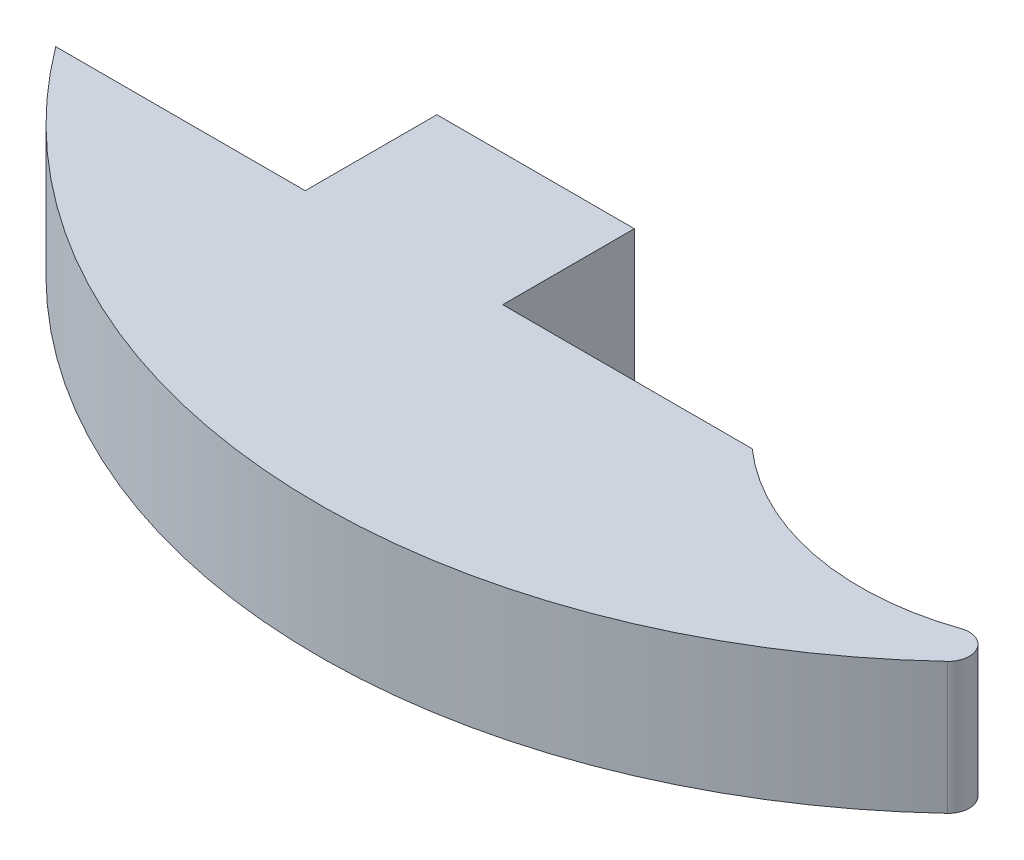
SolidWorks part; units mm, degrees
material "AISI 4130 Steel, annealed at 865C"
ref_plane "X-Y Datum" through (0, 0, 0) normal (0, 0, 1) x (1, 0, 0)
ref_plane "X-Z Datum" through (0, 0, 0) normal (0, 1, 0) x (1, 0, 0)
ref_plane "Y-Z Datum" through (0, 0, 0) normal (1, 0, 0) x (0, 0, -1)
sketch "Sketch1" plane through (0, 0, 0) normal (0, 1, 0) x (1, 0, 0)
  line L0 (-50.9024, -40.0059) -> (-57.5024, -40.0059) construction
  line L1 (-66.9024, -43.1809) -> (-20.6094, -43.1809)
  line L2 (-54.2024, -41.3694) -> (-54.2024, -38.6423) construction
  line L5 (-41.5024, -43.1809) -> (-66.9024, -43.1809)
  line L6 (-54.2024, -43.1809) -> (-54.2024, -48.3956) construction
  line L7 (-66.9024, -36.8309) -> (-66.9024, -43.1809)
  arc A3 (-12.2092, -46.3559) -> (-12.2092, -20.9559) centre (-12.2092, -33.6559) ccw construction
  arc A6 (-1.183, -39.9577) -> (-54.2024, -43.1809) centre (-28.7484, -24.2031) cw
  circle A7 centre (-12.2092, -33.6559) radius 12.7
  circle A8 centre (-12.2092, -33.6559) radius 12.7
  point P3 (-54.2024, -40.0059)
  point P11 (-15.8357, -44.7684)
  point P16 (-54.2024, -40.0059)
  dimension "D1" = 12.7
  dimension "D2" = 31.75
extrude "Boss-Extrude1" add sketch "Sketch1" along normal mid plane 6.35
sketch "Sketch2" plane through (0, 3.175, 0) normal (0, 1, 0) x (1, 0, 0)
  line L0 (-54.2024, -43.1809) -> (-20.6094, -43.1809) construction
  line L1 (-54.2024, -43.1809) -> (-20.6094, -43.1809)
  line L2 (-37.4059, -43.1809) -> (-37.4059, -36.8309) construction
  line L8 (-32.6434, -43.1809) -> (-42.1684, -43.1809)
  line L9 (-32.6434, -43.1809) -> (-32.6434, -36.8309)
  line L10 (-32.6434, -36.8309) -> (-42.1684, -36.8309)
  line L11 (-42.1684, -43.1809) -> (-42.1684, -36.8309)
  line L12 (-32.6434, -43.1809) -> (-42.1684, -36.8309) construction
  line L13 (-32.6434, -36.8309) -> (-42.1684, -43.1809) construction
  point P2 (-37.4059, -40.0059)
  dimension "D1" = 6.35
  dimension "D2" = 9.525
extrude "Boss-Extrude2" add sketch "Sketch2" against normal blind 6.35 contours L11 L1 L9 L10
sketch "Sketch3" plane through (0, 3.175, 0) normal (0, 1, 0) x (1, 0, 0)
  line L5 (-20.6094, -43.1809) -> (-32.6434, -43.1809)
  line L6 (-32.6434, -43.1809) -> (-32.6434, -36.8309)
  line L7 (-32.6434, -36.8309) -> (-42.1684, -36.8309)
  line L8 (-42.1684, -36.8309) -> (-42.1684, -43.1809)
  line L9 (-42.1684, -43.1809) -> (-54.2024, -43.1809)
  line L10 (-20.6094, -43.1809) -> (-32.6434, -43.1809)
  line L11 (-32.6434, -43.1809) -> (-32.6434, -36.8309)
  line L12 (-32.6434, -36.8309) -> (-42.1684, -36.8309)
  line L13 (-42.1684, -36.8309) -> (-42.1684, -43.1809)
  line L14 (-42.1684, -43.1809) -> (-54.2024, -43.1809)
  arc A1 (-7.0238, -47.357) -> (-8.0516, -45.6561) centre (-7.719, -46.6161) ccw
  arc A2 (-54.2024, -43.1809) -> (-1.183, -39.9577) centre (-28.7484, -24.2031) ccw
  arc A3 (-20.6094, -43.1809) -> (-1.183, -39.9577) centre (-12.2092, -33.6559) ccw
  arc A4 (-54.2024, -43.1809) -> (-7.0238, -47.357) centre (-28.7484, -24.2031) ccw
  arc A7 (-20.6094, -43.1809) -> (-8.0516, -45.6561) centre (-12.2092, -33.6559) ccw
  dimension "D2" = 1.016
  dimension "D1" = 0
extrude "Cut-Extrude1" cut sketch "Sketch3" against normal through all
